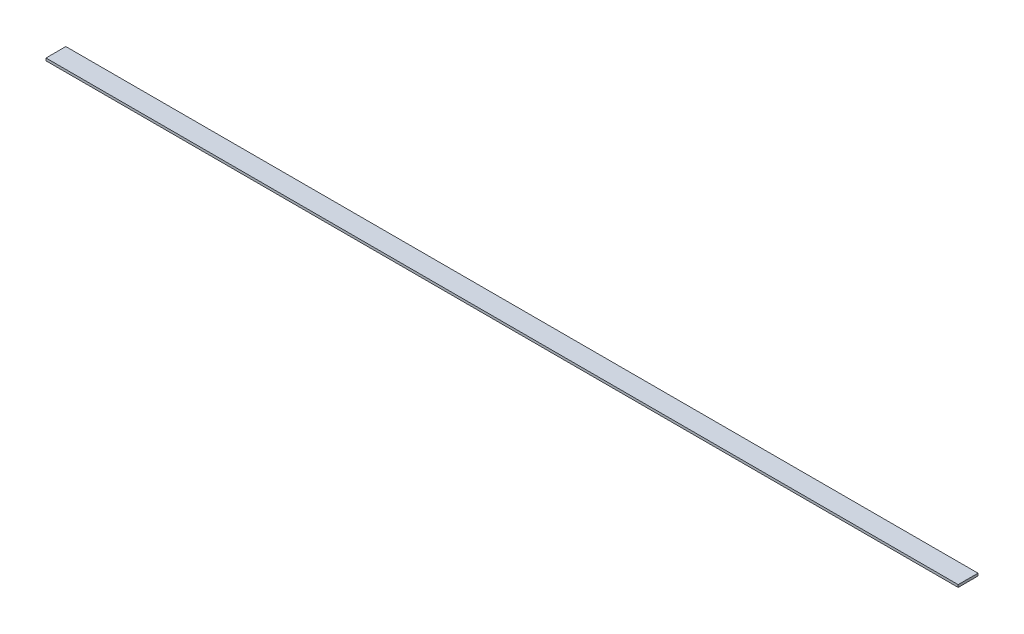
SolidWorks part; units mm, degrees
material "Very Low Density PE (SS)"
ref_plane "Front Plane" through (0, 0, 0) normal (0, 0, 1) x (1, 0, 0)
ref_plane "Top Plane" through (0, 0, 0) normal (0, 1, 0) x (1, 0, 0)
ref_plane "Right Plane" through (0, 0, 0) normal (1, 0, 0) x (0, 0, -1)
sketch "Sketch1" plane through (0, 0, 0) normal (0, 1, 0) x (1, 0, 0)
  line L1 (584.2, -12.7) -> (-584.2, -12.7)
  line L2 (584.2, -12.7) -> (584.2, 12.7)
  line L3 (584.2, 12.7) -> (-584.2, 12.7)
  line L4 (-584.2, -12.7) -> (-584.2, 12.7)
  line L5 (584.2, -12.7) -> (-584.2, 12.7) construction
  line L6 (584.2, 12.7) -> (-584.2, -12.7) construction
  point P0 (0, 0)
  dimension "D1" = 1168.4
  dimension "D2" = 25.4
extrude "Boss-Extrude1" add sketch "Sketch1" along normal blind 3.175
